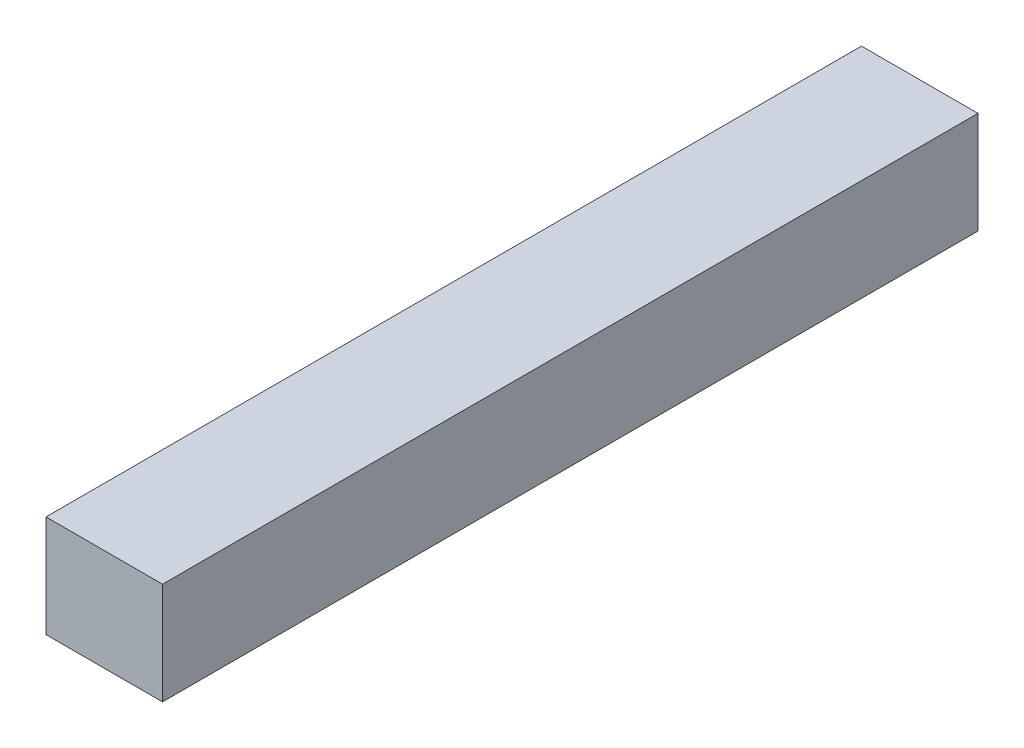
SolidWorks part; units mm, degrees
ref_plane "Front Plane" through (0, 0, 0) normal (0, 0, 1) x (1, 0, 0)
ref_plane "Top Plane" through (0, 0, 0) normal (0, 1, 0) x (1, 0, 0)
ref_plane "Right Plane" through (0, 0, 0) normal (1, 0, 0) x (0, 0, -1)
sketch "Sketch1" plane through (0, 0, 0) normal (0, 0, 1) x (1, 0, 0)
  line L1 (-4, 3.5) -> (4, 3.5)
  line L2 (-4, 3.5) -> (-4, -3.5)
  line L3 (-4, -3.5) -> (4, -3.5)
  line L4 (4, 3.5) -> (4, -3.5)
  line L5 (-4, 3.5) -> (4, -3.5) construction
  line L6 (-4, -3.5) -> (4, 3.5) construction
  point P0 (0, 0)
  dimension "D1" = 8
  dimension "D2" = 7
extrude "Boss-Extrude1" add sketch "Sketch1" along normal blind 56
